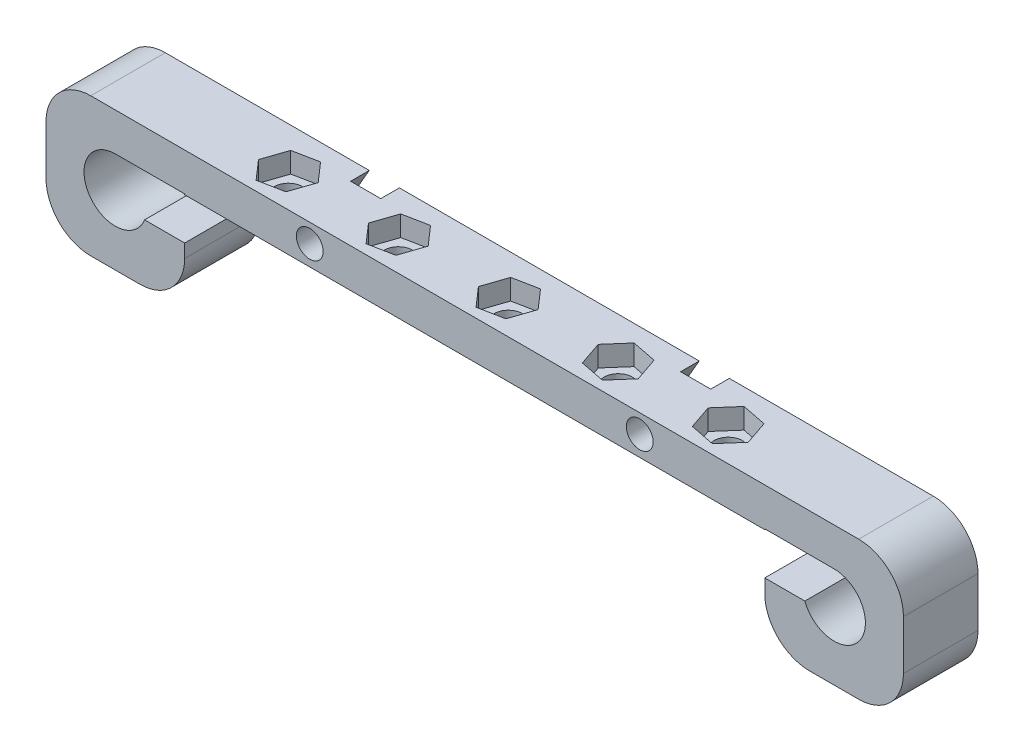
SolidWorks part; units mm, degrees
ref_plane "Alzado" through (0, 0, 0) normal (0, 0, 1) x (1, 0, 0)
ref_plane "Planta" through (0, 0, 0) normal (0, 1, 0) x (1, 0, 0)
ref_plane "Vista lateral" through (0, 0, 0) normal (1, 0, 0) x (0, 0, -1)
sketch "Croquis1" plane through (0, 0, 0) normal (0, 0, 1) x (1, 0, 0)
  line L0 (-48.2, 0) -> (48.2, 0) construction
  line L1 (-51.5, 9.3) -> (51.5, 9.3)
  line L2 (-57.5, 3.3) -> (-57.5, -3.3)
  line L3 (-51.5, -9.3) -> (51.5, -9.3)
  line L4 (57.5, 3.3) -> (57.5, -3.3)
  line L5 (-57.5, 9.3) -> (57.5, -9.3) construction
  line L6 (-57.5, -9.3) -> (57.5, 9.3) construction
  line L7 (-45.2641, 1.5) -> (-31.9, 1.5)
  line L8 (-31.9, 1.5) -> (-31.9, -9.3)
  line L9 (33.9, -1.5) -> (33.9, -9.3)
  line L10 (0, 9.3) -> (0, -9.3) construction
  line L11 (-46.3533, -1.5) -> (-33.9, -1.5)
  line L12 (-33.9, -1.5) -> (-33.9, -9.3)
  line L13 (31.9, 1.5) -> (31.9, -9.3)
  line L14 (46.3533, -1.5) -> (33.9, -1.5)
  line L15 (45.2641, 1.5) -> (31.9, 1.5)
  line L16 (-57.439, 24.5025) -> (-57.439, -43.5519) construction
  line L17 (38.9, -3.3) -> (38.9, -1.5)
  line L18 (58.0207, -15.7775) -> (58.0207, 36.8628) construction
  line L19 (48.2, 4.2) -> (38.9, 4.2)
  line L20 (-38.9, -3.3) -> (-38.9, -1.5)
  line L21 (-38.9, 4.2) -> (-48.2, 4.2)
  line L23 (-38.9, 4.2) -> (-38.9, 4.3)
  line L24 (-38.9, 4.3) -> (38.9, 4.3)
  line L25 (38.9, 4.2) -> (38.9, 4.3)
  circle A0 centre (-48.2, 0) radius 4.2
  circle A1 centre (48.2, 0) radius 4.2
  arc A2 (51.5, 9.3) -> (57.5, 3.3) centre (51.5, 3.3) cw
  arc A3 (57.5, -3.3) -> (51.5, -9.3) centre (51.5, -3.3) cw
  arc A4 (-57.5, -3.3) -> (-51.5, -9.3) centre (-51.5, -3.3) ccw
  arc A5 (-51.5, 9.3) -> (-57.5, 3.3) centre (-51.5, 3.3) ccw
  arc A6 (38.9, -3.3) -> (44.9, -9.3) centre (44.9, -3.3) ccw
  arc A7 (-38.9, -3.3) -> (-44.9, -9.3) centre (-44.9, -3.3) cw
  point P0 (0, 0)
  dimension "D3" = 8.4
  dimension "D4" = 8.4
  dimension "D7" = 6
  dimension "D8" = 1.5
  dimension "D13" = 6.6
  dimension "D14" = 12
  dimension "D1" = 96.4
  dimension "D2" = 48.2
  dimension "D5" = 115
  dimension "D6" = 18.6
  dimension "D9" = 1.5
  dimension "D10" = 9.3
  dimension "D11" = 16.3
  dimension "D12" = 2
  dimension "D15" = 0.1
extrude "Saliente-Extruir1" add sketch "Croquis1" along normal blind 10
sketch "Croquis9" plane through (0, 4.3, 0) normal (0, -1, 0) x (-1, 0, 0)
  line L0 (-34.4981, -5.5) -> (34.4981, -5.5) construction
  line L2 (38.9, 0) -> (-38.9, 0) construction
  circle A0 centre (0, -5.5) radius 1.9
  circle A1 centre (-29.4981, -5.5) radius 1.9
  circle A2 centre (-14.7481, -5.5) radius 1.9
  circle A3 centre (14.7481, -5.5) radius 1.9
  circle A4 centre (29.4981, -5.5) radius 1.9
  dimension "D1" = 5.5
  dimension "D3" = 5
  dimension "D4" = 5
  dimension "D5" = 14.75
  dimension "D6" = 14.75
extrude "Cortar-Extruir5" cut sketch "Croquis9" against normal through all
sketch "Croquis10" plane through (0, 9.3, 0) normal (0, -1, 0) x (1, 0, 0)
  line L1 (1.0984, 2.2756) -> (3.3416, 4.839)
  line L2 (3.3416, 4.839) -> (2.2433, 8.0634)
  line L3 (2.2433, 8.0634) -> (-1.0984, 8.7244)
  line L4 (-1.0984, 8.7244) -> (-3.3416, 6.161)
  line L5 (-3.3416, 6.161) -> (-2.2433, 2.9366)
  line L6 (-2.2433, 2.9366) -> (1.0984, 2.2756)
  line L7 (13.6497, 2.2756) -> (16.9913, 2.9366)
  line L8 (16.9913, 2.9366) -> (18.0897, 6.161)
  line L9 (18.0897, 6.161) -> (15.8464, 8.7244)
  line L10 (15.8464, 8.7244) -> (12.5048, 8.0634)
  line L11 (12.5048, 8.0634) -> (11.4065, 4.839)
  line L12 (11.4065, 4.839) -> (13.6497, 2.2756)
  line L13 (28.3997, 2.2756) -> (31.7413, 2.9366)
  line L14 (31.7413, 2.9366) -> (32.8397, 6.161)
  line L15 (32.8397, 6.161) -> (30.5964, 8.7244)
  line L16 (30.5964, 8.7244) -> (27.2548, 8.0634)
  line L17 (27.2548, 8.0634) -> (26.1565, 4.839)
  line L18 (26.1565, 4.839) -> (28.3997, 2.2756)
  line L19 (-13.6497, 2.2756) -> (-11.4065, 4.839)
  line L20 (-11.4065, 4.839) -> (-12.5048, 8.0634)
  line L21 (-12.5048, 8.0634) -> (-15.8464, 8.7244)
  line L22 (-15.8464, 8.7244) -> (-18.0897, 6.161)
  line L23 (-18.0897, 6.161) -> (-16.9913, 2.9366)
  line L24 (-16.9913, 2.9366) -> (-13.6497, 2.2756)
  line L25 (-28.3997, 2.2756) -> (-26.1565, 4.839)
  line L26 (-26.1565, 4.839) -> (-27.2548, 8.0634)
  line L27 (-27.2548, 8.0634) -> (-30.5964, 8.7244)
  line L28 (-30.5964, 8.7244) -> (-32.8397, 6.161)
  line L29 (-32.8397, 6.161) -> (-31.7413, 2.9366)
  line L30 (-31.7413, 2.9366) -> (-28.3997, 2.2756)
  circle A0 centre (0, 5.5) radius 2.95 construction
  circle A1 centre (14.7481, 5.5) radius 2.95 construction
  circle A2 centre (29.4981, 5.5) radius 2.95 construction
  circle A3 centre (-14.7481, 5.5) radius 2.95 construction
  circle A4 centre (-29.4981, 5.5) radius 2.95 construction
  dimension "D1" = 5.9
  dimension "D2" = 5.9
  dimension "D3" = 5.9
  dimension "D4" = 5.9
  dimension "D5" = 5.9
extrude "Cortar-Extruir6" cut sketch "Croquis10" along normal blind 2.75
sketch "Croquis11" plane through (0, 4.3, 0) normal (0, -1, 0) x (1, 0, 0)
  line L0 (38.9, 10) -> (38.9, 0) construction
  line L1 (-38.9, 10) -> (38.9, 10)
  line L2 (-38.9, 10) -> (-38.9, 8.5)
  line L3 (-38.9, 8.5) -> (38.9, 8.5)
  line L4 (38.9, 10) -> (38.9, 8.5)
  circle A0 centre (-29.4981, 5.5) radius 1.9 construction
  dimension "D1" = 3
extrude "Saliente-Extruir2" add sketch "Croquis11" along normal blind 0.2
sketch "Croquis12" plane through (0, 0, 0) normal (0, 0, -1) x (-1, 0, 0)
  line L1 (25.5891, 6.8) -> (23.8571, 9.8)
  line L2 (38.9, 4.3) -> (-38.9, 4.3) construction
  line L3 (51.5, 9.3) -> (-51.5, 9.3) construction
  line L4 (23.8571, 9.8) -> (20.3929, 9.8)
  line L5 (20.3929, 9.8) -> (18.6609, 6.8)
  line L6 (18.6609, 6.8) -> (20.3929, 3.8)
  line L7 (20.3929, 3.8) -> (23.8571, 3.8)
  line L8 (23.8571, 3.8) -> (25.5891, 6.8)
  line L9 (-18.6659, 6.8) -> (-20.3979, 9.8)
  line L10 (-20.3979, 9.8) -> (-23.8621, 9.8)
  line L11 (-23.8621, 9.8) -> (-25.5941, 6.8)
  line L12 (-25.5941, 6.8) -> (-23.8621, 3.8)
  line L13 (-23.8621, 3.8) -> (-20.3979, 3.8)
  line L14 (-20.3979, 3.8) -> (-18.6659, 6.8)
  circle A2 centre (22.125, 6.8) radius 3 construction
  circle A3 centre (-22.13, 6.8) radius 3 construction
  dimension "D1" = 22.125
  dimension "D2" = 22.13
  dimension "D3" = 2.5
  dimension "D4" = 2.5
  dimension "D5" = 2.5
  dimension "D6" = 2.5
  dimension "D7" = 6
  dimension "D8" = 6
extrude "Cortar-Extruir7" cut sketch "Croquis12" against normal blind 2.5
sketch "Croquis13" plane through (0, 0, 2.5) normal (0, 0, -1) x (-1, 0, 0)
  line L0 (25.5891, 6.8) -> (18.6609, 6.8) construction
  line L2 (-18.6659, 6.8) -> (-25.5941, 6.8) construction
  circle A0 centre (22.125, 6.8) radius 1.8
  circle A1 centre (-22.13, 6.8) radius 1.8
extrude "Cortar-Extruir8" cut sketch "Croquis13" against normal through all
